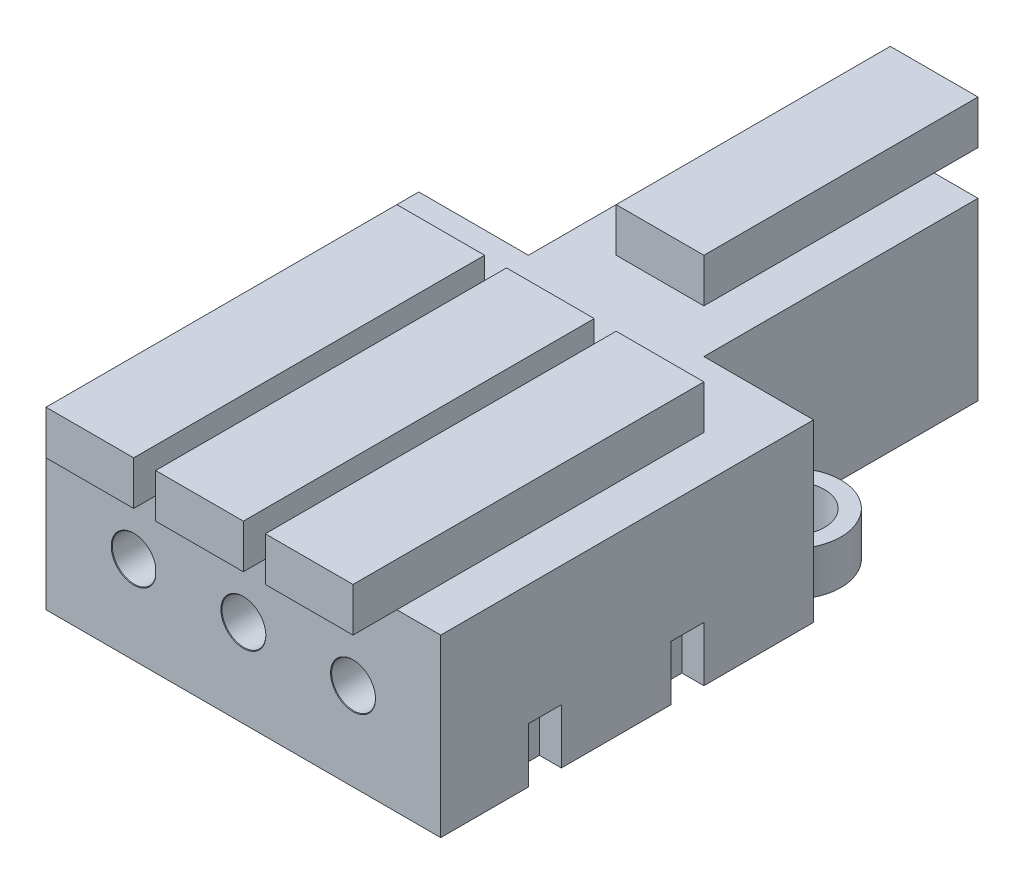
SolidWorks part; units mm, degrees
material "ABS"
ref_plane "Front Plane" through (0, 0, 0) normal (0, 0, 1) x (1, 0, 0)
ref_plane "Top Plane" through (0, 0, 0) normal (0, 1, 0) x (1, 0, 0)
ref_plane "Right Plane" through (0, 0, 0) normal (1, 0, 0) x (0, 0, -1)
sketch "Sketch1" plane through (0, 0, 0) normal (0, 1, 0) x (1, 0, 0)
  line L1 (0, 0) -> (8, 0)
  line L2 (0, 0) -> (0, 17)
  line L3 (0, 17) -> (8, 17)
  line L4 (8, 0) -> (8, 17)
  dimension "D1" = 8
  dimension "D2" = 17
extrude "connector_body" add sketch "Sketch1" along normal blind 8
sketch "Sketch2" plane through (0, 0, 0) normal (0, 0, -1) x (-1, 0, 0)
  line L0 (0, 8) -> (0, 0) construction
  line L1 (-8, 8) -> (0, 8) construction
  point P0 (-4, 4)
  dimension "D1" = 4
  dimension "D2" = 4
hole_wizard "cable_hole" positions "Sketch2" profile "Sketch3" hole size "Ø2.0" standard "DIN"
sketch "Sketch3" plane through (4, 4, 0) normal (1, 0, 0) x (0, -1, 0)
  line L0 (0, 0) -> (0, 10.6009)
  line L1 (0, 10.6009) -> (1, 10)
  line L2 (1, 10) -> (1, 0.025)
  line L3 (1, 0.025) -> (1.025, 0)
  line L5 (1.025, 0) -> (0, 0)
  line L6 (-1, 0.025) -> (-1.025, 0) construction
  line L10 (0, 10.6009) -> (-1, 10) construction
  line L11 (0, -6.35) -> (0, 107.95) construction
  dimension "Hole Dia." = 2
  dimension "Hole Depth" = 10
  dimension "Near C'Sink Dia." = 2.05
  dimension "Near C'Sink Angle" = 90
  dimension "Drill Angle" = 118
sketch "Sketch4" plane through (0, 8, 0) normal (0, 1, 0) x (1, 0, 0)
  line L0 (8, 0) -> (8, 17) construction
  line L1 (2, 14) -> (6, 14)
  line L2 (2, 14) -> (2, -2)
  line L3 (2, -2) -> (6, -2)
  line L4 (6, 14) -> (6, -2)
  line L6 (8, 17) -> (0, 17) construction
  dimension "D1" = 4
  dimension "D2" = 2
  dimension "D3" = 3
  dimension "D4" = 16
extrude "clamp" add sketch "Sketch4" along normal blind 2
pattern_linear "connector_pattern" count 3 spacing 5 along (1, 0, 0) of "connector_body", "cable_hole", "clamp"
sketch "Sketch5" plane through (0, 8, 0) normal (0, 1, 0) x (1, 0, 0)
  line L0 (18, 17) -> (0, 17) construction
  line L1 (5, 17) -> (13, 17)
  line L2 (5, 17) -> (5, 29.5)
  line L3 (5, 29.5) -> (13, 29.5)
  line L4 (13, 17) -> (13, 29.5)
  line L5 (0, 17) -> (0, 0) construction
  dimension "D1" = 8
  dimension "D2" = 5
  dimension "D3" = 12.5
extrude "single_body" add sketch "Sketch5" against normal up to vertex (8 mm away)
sketch "Sketch6" plane through (0, 0, 0) normal (-1, 0, 0) x (0, 0, 1)
  line L0 (-17, 0) -> (0, 0) construction
  line L1 (-12, 0) -> (-10.5, 0)
  line L2 (-12, 0) -> (-12, 2.5004)
  line L3 (-12, 2.5004) -> (-10.5, 2.5004)
  line L4 (-10.5, 0) -> (-10.5, 2.5004)
  line L5 (-17, 0) -> (-17, 8) construction
  line L6 (-5.5, 0) -> (-4, 0)
  line L7 (-5.5, 0) -> (-5.5, 2.5004)
  line L8 (-5.5, 2.5004) -> (-4, 2.5004)
  line L9 (-4, 0) -> (-4, 2.5004)
  point P12 (-4.75, 0)
  dimension "D1" = 5
  dimension "D2" = 1.5
  dimension "D3" = 1.5
  dimension "D4" = 2.5004
  dimension "D5" = 5
extrude "chaining_nobs" add sketch "Sketch6" along normal blind 1
sketch "Sketch7" plane through (0, 0, 0) normal (0, -1, 0) x (1, 0, 0)
  line L1 (18, -4) -> (17, -4)
  line L2 (18, -4) -> (18, -5.5)
  line L3 (18, -5.5) -> (17, -5.5)
  line L4 (17, -4) -> (17, -5.5)
  line L5 (-1, -10.5) -> (0, -10.5) construction
  line L6 (17, -12) -> (18, -12)
  line L7 (17, -12) -> (17, -10.5)
  line L8 (17, -10.5) -> (18, -10.5)
  line L9 (18, -12) -> (18, -10.5)
  line L10 (18, 0) -> (18, -17) construction
  line L11 (-1, -5.5) -> (0, -5.5) construction
  dimension "D1" = 1
  dimension "D2" = 1.5
sketch "Sketch8" plane through (0, 8, 0) normal (0, 1, 0) x (1, 0, 0)
  line L0 (5, 29.5) -> (5, 17) construction
  line L1 (7, 19) -> (11, 19)
  line L2 (7, 19) -> (7, 31.5)
  line L3 (7, 31.5) -> (11, 31.5)
  line L4 (11, 19) -> (11, 31.5)
  line L5 (18, 17) -> (13, 17) construction
  line L6 (13, 29.5) -> (5, 29.5) construction
  dimension "D1" = 4
  dimension "D2" = 2
  dimension "D3" = 2
  dimension "D4" = 2
extrude "chaining_nobs_cutout" cut sketch "Sketch7" against normal up to vertex (2.5004 mm away)
extrude "single_body_clamp" add sketch "Sketch8" along normal up to vertex (2 mm away)
sketch "Sketch9" plane through (0, 0, 0) normal (0, -1, 0) x (1, 0, 0)
  line L1 (5, -29.5) -> (5, -17) construction
  line L2 (13, -29.5) -> (5, -29.5) construction
  circle A0 centre (3, -19) radius 2.25
  circle A1 centre (3, -19) radius 1.5
  circle A2 centre (15, -19) radius 1.5
  circle A3 centre (15, -19) radius 2.25
  dimension "D2" = 2
  dimension "D3" = 4.5
  dimension "D4" = 3
  dimension "D1" = 12
  dimension "D5" = 10.5
extrude "mounting_rings" add sketch "Sketch9" against normal blind 2
